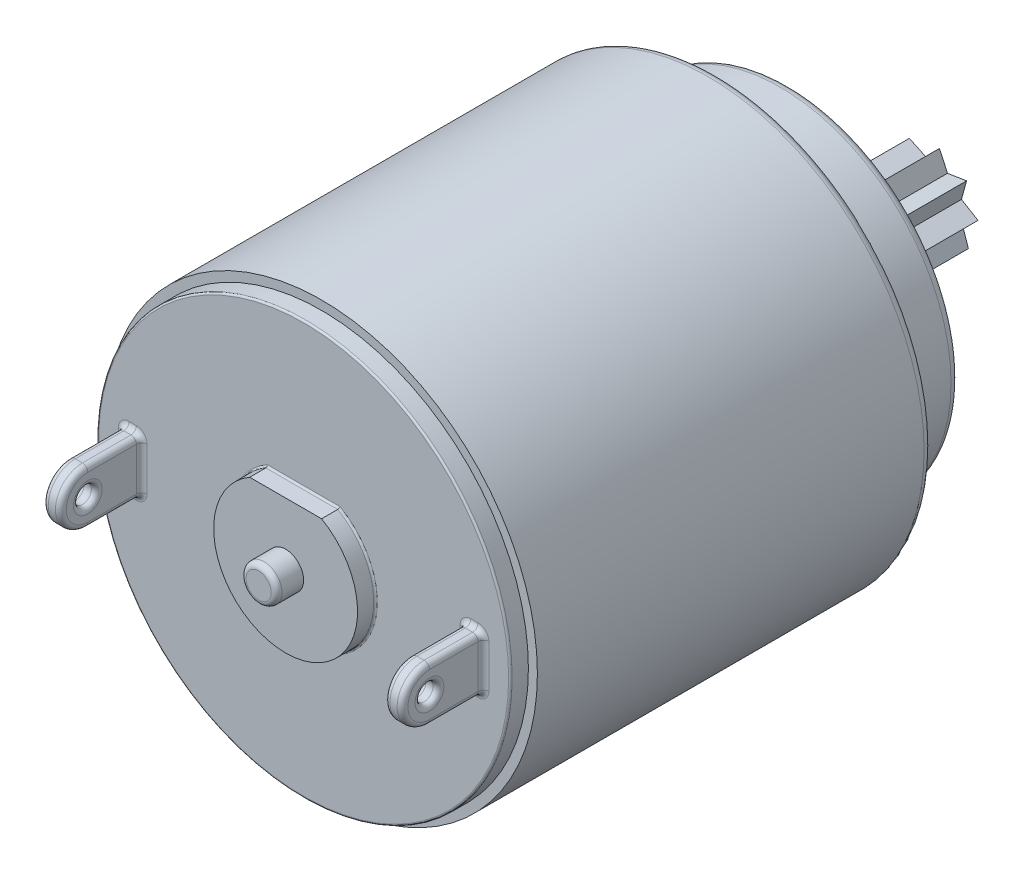
SolidWorks part; units mm, degrees
ref_plane "Спереди" through (0, 0, 0) normal (0, 0, 1) x (1, 0, 0)
ref_plane "Сверху" through (0, 0, 0) normal (0, 1, 0) x (1, 0, 0)
ref_plane "Справа" through (0, 0, 0) normal (1, 0, 0) x (0, 0, -1)
sketch "Эскиз1" plane through (0, 0, 0) normal (0, 0, 1) x (1, 0, 0)
  circle A0 centre (0, 0) radius 12
  dimension "D1" = 24
extrude "Бобышка-Вытянуть1" add sketch "Эскиз1" along normal blind 22
sketch "Эскиз2" plane through (0, 0, 22) normal (0, 0, 1) x (1, 0, 0)
  circle A0 centre (0, 0) radius 11.5
  dimension "D1" = 23
extrude "Бобышка-Вытянуть2" add sketch "Эскиз2" along normal blind 1
sketch "Эскиз3" plane through (0, 0, 23) normal (0, 0, 1) x (1, 0, 0)
  line L0 (-2, 3.4641) -> (2, 3.4641)
  arc A0 (-2, 3.4641) -> (2, 3.4641) centre (0, 0) ccw
  dimension "D2" = 4
extrude "Бобышка-Вытянуть3" add sketch "Эскиз3" along normal blind 1 contours L0 A0
sketch "Эскиз4" plane through (0, 0, 24) normal (0, 0, 1) x (1, 0, 0)
  circle A0 centre (0, 0) radius 1
  dimension "D1" = 2
extrude "Бобышка-Вытянуть4" add sketch "Эскиз4" along normal blind 1.5
sketch "Эскиз5" plane through (0, 0, 23) normal (0, 0, 1) x (1, 0, 0)
  line L0 (0, 12.6557) -> (0, -13.5005) construction
  line L1 (10, -1.5) -> (9, -1.5)
  line L2 (-10, 1.5) -> (-9, 1.5)
  line L3 (-10, 1.5) -> (-10, -1.5)
  line L4 (-10, -1.5) -> (-9, -1.5)
  line L5 (-9, 1.5) -> (-9, -1.5)
  line L6 (10, 1.5) -> (10, -1.5)
  line L7 (10, 1.5) -> (9, 1.5)
  line L8 (9, 1.5) -> (9, -1.5)
  dimension "D1" = 9
  dimension "D2" = 3
  dimension "D3" = 1
  dimension "D4" = 1.5
extrude "Бобышка-Вытянуть5" add sketch "Эскиз5" along normal blind 3
sketch "Эскиз6" plane through (10, 0, 0) normal (1, 0, 0) x (0, 0, -1)
  line L0 (-26, -1.5) -> (-26, 1.5) construction
  circle A0 centre (-26, 0) radius 1.5
extrude "Бобышка-Вытянуть6" add sketch "Эскиз6" against normal blind 1
sketch "Эскиз7" plane through (10, 0, 0) normal (1, 0, 0) x (0, 0, -1)
  circle A0 centre (-26, 0) radius 0.5
  dimension "D1" = 1
  dimension "D2" = 1.5
  dimension "D3" = 1.5
extrude "Вырез-Вытянуть1" cut sketch "Эскиз7" against normal blind 1
mirror "Зеркальное отражение5" about plane through (0, 0, 0) normal (1, 0, 0) of "Вырез-Вытянуть1", "Бобышка-Вытянуть6"
fillet "Скругление3" radius 0.3 24 edges at (9.5, -1.5, 23) (9.5, 1.5, 23) (-9.5, -1.5, 23) (-9.5, 1.5, 23) (9, 0, 23) (9, 1.5, 24.5) (9, 0, 27.5) (10, 0, 27.5) (9, -1.5, 24.5) (9, 0, 25.5) (10, 0, 23) (10, -1.5, 24.5) (10, 1.5, 24.5) (10, 0, 25.5) (-9, 1.5, 24.5) (-9, 0, 23) (-9, -1.5, 24.5) (-10, 0, 27.5) (-9, 0, 27.5) (-10, -1.5, 24.5) (-10, 0, 23) (-10, 1.5, 24.5) (-9, 0, 25.5) (-10, 0, 25.5)
fillet "Скругление4" radius 0.3 1 edges at (1, 0, 25.5)
fillet "Скругление5" radius 0.1 3 edges at (11.5, 0, 23) (0, -4, 23) (0, 3.4641, 23)
sketch "Эскиз8" plane through (0, 0, 0) normal (0, 0, -1) x (-1, 0, 0)
  circle A0 centre (0, 0) radius 9.5
  dimension "D1" = 19
extrude "Бобышка-Вытянуть7" add sketch "Эскиз8" along normal blind 4
sketch "Эскиз9" plane through (0, 0, -4) normal (0, 0, -1) x (-1, 0, 0)
  circle A0 centre (0, 0) radius 3
  dimension "D1" = 6
extrude "Бобышка-Вытянуть8" add sketch "Эскиз9" along normal blind 1
sketch "Эскиз10" plane through (0, 0, -5) normal (0, 0, -1) x (-1, 0, 0)
  circle A0 centre (0, 0) radius 1
  dimension "D1" = 2
extrude "Бобышка-Вытянуть9" add sketch "Эскиз10" along normal blind 7
sketch "Эскиз11" plane through (0, 0, -12) normal (0, 0, -1) x (-1, 0, 0)
  line L0 (-0.5124, -2.4469) -> (0.2422, -1.6861)
  line L9 (-0.8042, 1.5016) -> (-0.3554, 2.4746)
  line L19 (-0.3554, 2.4746) -> (0.3491, 1.6672)
  line L20 (0.3491, 1.6672) -> (1.3184, 2.1241)
  line L21 (1.3184, 2.1241) -> (1.3391, 1.0527)
  line L22 (2.3753, 0.7797) -> (1.3391, 1.0527)
  line L23 (1.7025, -0.0543) -> (2.3753, 0.7797)
  line L24 (1.7025, -0.0543) -> (2.3208, -0.9295)
  line L25 (2.3208, -0.9295) -> (1.2693, -1.1359)
  line L26 (1.2693, -1.1359) -> (1.1803, -2.2038)
  line L27 (1.1803, -2.2038) -> (0.2422, -1.6861)
  line L30 (-0.5124, -2.4469) -> (-0.8983, -1.4473)
  line L31 (-1.9654, -1.5451) -> (-0.8983, -1.4473)
  line L32 (-1.6184, -0.5313) -> (-1.9654, -1.5451)
  line L33 (-2.4987, 0.0797) -> (-1.6184, -0.5313)
  line L34 (-1.5813, 0.6333) -> (-2.4987, 0.0797)
  line L35 (-1.8629, 1.6672) -> (-1.5813, 0.6333)
  line L36 (-1.8629, 1.6672) -> (-0.8042, 1.5016)
extrude "Бобышка-Вытянуть10" add sketch "Эскиз11" against normal blind 4
fillet "Скругление6" radius 0.5 3 edges at (12, 0, 0) (9.5, 0, 0) (-9.5, 0, -4)
